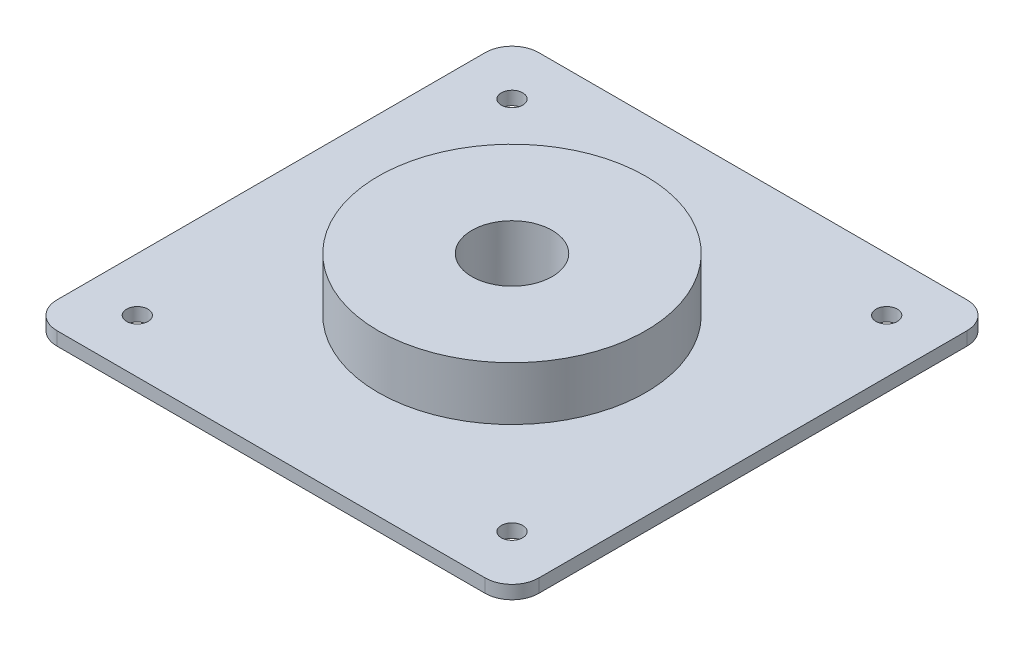
SolidWorks part; units mm, degrees
ref_plane "Front" through (0, 0, 0) normal (0, 0, 1) x (1, 0, 0)
ref_plane "Top" through (0, 0, 0) normal (0, 1, 0) x (1, 0, 0)
ref_plane "Right" through (0, 0, 0) normal (1, 0, 0) x (0, 0, -1)
sketch "Sketch1" plane through (0, 0, 0) normal (0, 1, 0) x (1, 0, 0)
  line L0 (10, 0) -> (170, 0)
  line L1 (0, 10) -> (0, 170)
  line L2 (10, 180) -> (170, 180)
  line L3 (180, 170) -> (180, 10)
  arc A0 (170, 180) -> (180, 170) centre (170, 170) cw
  arc A1 (180, 10) -> (170, 0) centre (170, 10) cw
  arc A2 (10, 0) -> (0, 10) centre (10, 10) cw
  arc A3 (10, 180) -> (0, 170) centre (10, 170) ccw
  point P9 (180, 0)
  point P12 (0, 0)
  point P15 (0, 180)
  dimension "D3" = 10
  dimension "D1" = 180
  dimension "D2" = 180
extrude "Boss-Extrude1" add sketch "Sketch1" along normal blind 5
sketch "Sketch2" plane through (0, 5, 0) normal (0, 1, 0) x (1, 0, 0)
  line L0 (0, 25.4481) -> (20, 25.4481) construction
  line L1 (0, 170) -> (0, 10) construction
  line L2 (20, 0) -> (20, 20) construction
  line L3 (10, 0) -> (170, 0) construction
  circle A0 centre (20, 20) radius 4
  dimension "10" = 8
  dimension "D1" = 20
  dimension "D2" = 20
extrude "Cut-Extrude1" cut sketch "Sketch2" against normal blind 10
pattern_linear "LPattern1" count 2 spacing 140 along (1, 0, 0) count 2 spacing 140 along (0, 0, -1) of "Cut-Extrude1"
sketch "Sketch3" plane through (0, 5, 0) normal (0, 1, 0) x (1, 0, 0)
  line L0 (90, 180) -> (90, 0) construction
  line L1 (170, 180) -> (10, 180) construction
  line L2 (10, 0) -> (170, 0) construction
  circle A0 centre (90, 90) radius 50
  dimension "D1" = 100
extrude "Boss-Extrude2" add sketch "Sketch3" along normal blind 20 contours A0
sketch "Sketch5" plane through (0, 25, 0) normal (0, 1, 0) x (1, 0, 0)
  line L0 (90, 140) -> (90, 40) construction
  circle A0 centre (90, 90) radius 50 construction
  circle A1 centre (90, 90) radius 50 construction
  circle A2 centre (90, 90) radius 15
  dimension "D1" = 30
extrude "Cut-Extrude3" cut sketch "Sketch5" against normal blind 50
